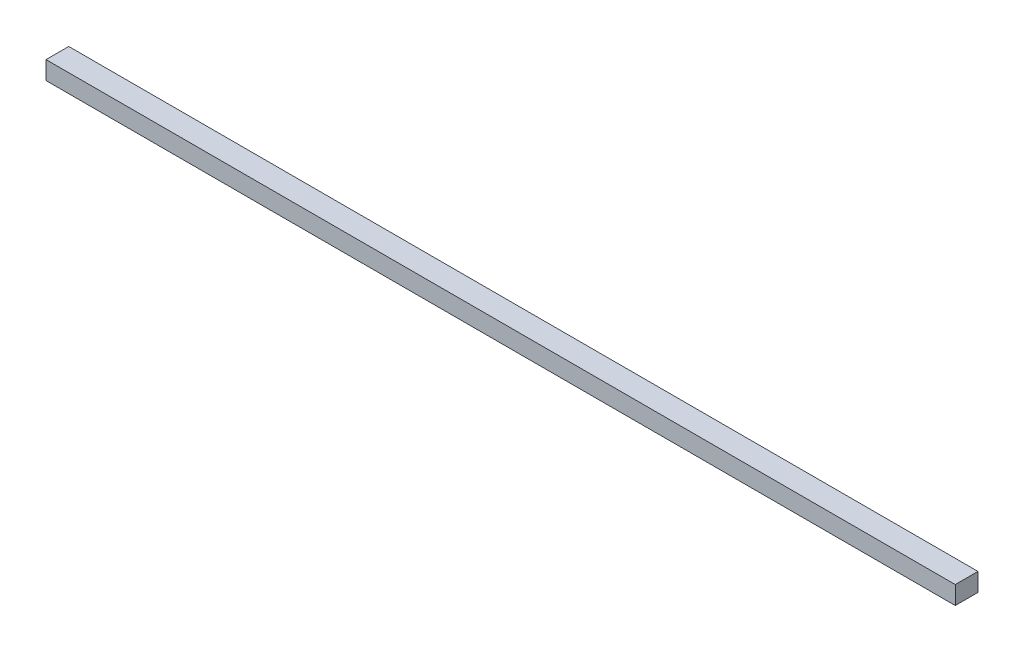
SolidWorks part; units mm, degrees
ref_plane "前视基准面" through (0, 0, 0) normal (0, 0, 1) x (1, 0, 0)
ref_plane "上视基准面" through (0, 0, 0) normal (0, 1, 0) x (1, 0, 0)
ref_plane "右视基准面" through (0, 0, 0) normal (1, 0, 0) x (0, 0, -1)
other "Configuration Table"
sketch "草图1" plane through (0, 0, 0) normal (1, 0, 0) x (0, 0, -1)
  line L1 (0, 0) -> (-20, 0)
  line L2 (0, 0) -> (0, 16)
  line L3 (0, 16) -> (-20, 16)
  line L4 (-20, 0) -> (-20, 16)
  dimension "D1" = 20
  dimension "D2" = 16
extrude "凸台-拉伸1" add sketch "草图1" along normal blind 800
